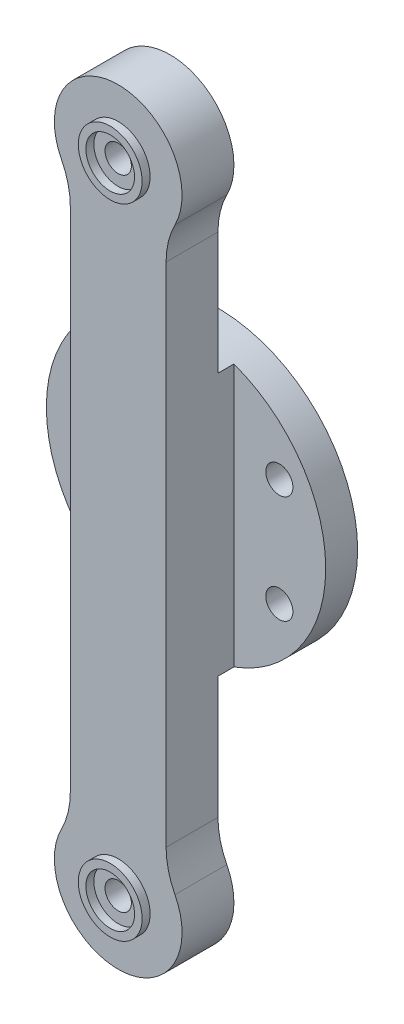
SolidWorks part; units mm, degrees
ref_plane "前视基准面" through (0, 0, 0) normal (0, 0, 1) x (1, 0, 0)
ref_plane "上视基准面" through (0, 0, 0) normal (0, 1, 0) x (1, 0, 0)
ref_plane "右视基准面" through (0, 0, 0) normal (1, 0, 0) x (0, 0, -1)
sketch "草图1" plane through (0, 0, 0) normal (0, 1, 0) x (1, 0, 0)
  line L0 (17.5, 4) -> (0, 4)
  line L1 (0, 4) -> (0, 0)
  line L2 (0, 0) -> (17.5, 0)
  line L3 (17.5, 0) -> (17.5, 4)
  line L4 (0, 4) -> (0, 0) construction
revolve "旋转1" add sketch "草图1" angle 360 about L4
sketch "草图2" plane through (0, 0, 0) normal (0, 0, 1) x (1, 0, 0)
  line L0 (6, 16.4393) -> (6, -16.4393)
  line L1 (-6, -16.4393) -> (-6, 16.4393)
  arc A0 (6, -16.4393) -> (-6, -16.4393) centre (0, 0) cw
  arc A1 (-6, 16.4393) -> (6, 16.4393) centre (0, 0) cw
extrude "凸台-拉伸1" add sketch "草图2" along normal blind 2
sketch "草图3" plane through (0, 0, 2) normal (0, 0, 1) x (1, 0, 0)
  line L0 (-6, -34.7085) -> (-6, 34.7085)
  line L1 (6, 34.7085) -> (6, -34.7085)
  arc A0 (6, -34.7085) -> (-6, -34.7085) centre (0, -40) cw
  arc A1 (-6, 34.7085) -> (6, 34.7085) centre (0, 40) cw
extrude "凸台-拉伸2" add sketch "草图3" along normal blind 6.5
ref_plane "基准面1" through (0, -40, 0) normal (0, -1, 0) x (1, 0, 0)
sketch "草图4" plane through (0, -40, 0) normal (0, -1, 0) x (1, 0, 0)
  line L0 (4, 9.5) -> (0, 9.5)
  line L1 (0, 9.5) -> (0, 8.5)
  line L2 (0, 8.5) -> (4, 8.5)
  line L3 (4, 8.5) -> (4, 9.5)
  line L4 (0, 9.5) -> (0, 8.5) construction
revolve "旋转2" add sketch "草图4" angle 360 about L4
ref_plane "基准面2" through (0, 40, 0) normal (0, -1, 0) x (1, 0, 0)
sketch "草图5" plane through (0, 40, 0) normal (0, -1, 0) x (1, 0, 0)
  line L0 (4, 9.5) -> (0, 9.5)
  line L1 (0, 9.5) -> (0, 8.5)
  line L2 (0, 8.5) -> (4, 8.5)
  line L3 (4, 8.5) -> (4, 9.5)
  line L4 (0, 9.5) -> (0, 8.5) construction
revolve "旋转3" add sketch "草图5" angle 360 about L4
hole_wizard "Ø3.4 (3.4) 直径孔1" positions "草图7" profile "草图6" hole size "Ø3.4" standard "ANSI Metric"
sketch "草图7" plane through (0, 0, -4) normal (0, 0, -1) x (-1, 0, 0)
  point P0 (11.6913, 6.75)
  point P1 (11.6913, -6.75)
  point P2 (-11.6913, -6.75)
  point P3 (-11.6913, 6.75)
sketch "草图6" plane through (-11.6913, 6.75, -4) normal (1, 0, 0) x (0, 1, 0)
  line L0 (0, 0) -> (0, 13.5)
  line L1 (0, 13.5) -> (1.7, 13.5)
  line L2 (1.7, 13.5) -> (1.7, 0)
  line L5 (1.7, 0) -> (0, 0)
  line L11 (0, -6.35) -> (0, 107.95) construction
  dimension "通孔孔直径" = 3.4
  dimension "通孔孔深度" = 13.5
hole_wizard "M3 六角头机械螺钉的柱形沉头孔1" positions "草图9" profile "草图8" counterbore size "M3" standard "ANSI Metric"
sketch "草图9" plane through (0, 0, 9.5) normal (0, 0, 1) x (1, 0, 0)
  point P0 (0, -40)
  point P1 (0, 40)
sketch "草图8" plane through (0, -40, 9.5) normal (1, 0, 0) x (0, -1, 0)
  line L0 (0, 0) -> (0, 13.5)
  line L1 (0, 13.5) -> (1.65, 13.5)
  line L3 (1.65, 13.5) -> (1.65, 1)
  line L4 (1.65, 1) -> (3.05, 1)
  line L5 (3.05, 1) -> (3.05, 0)
  line L7 (3.05, 0) -> (0, 0)
  line L11 (0, -6.35) -> (0, 107.95) construction
  dimension "通孔孔直径" = 3.3
  dimension "通孔孔深度" = 13.5
  dimension "柱形沉头孔直径" = 6.1
  dimension "柱形沉头孔深度" = 1
fillet "圆角1" radius 10 4 edges at (-6, -34.7085, 5.25) (-6, 34.7085, 5.25) (6, -34.7085, 5.25) (6, 34.7085, 5.25)
